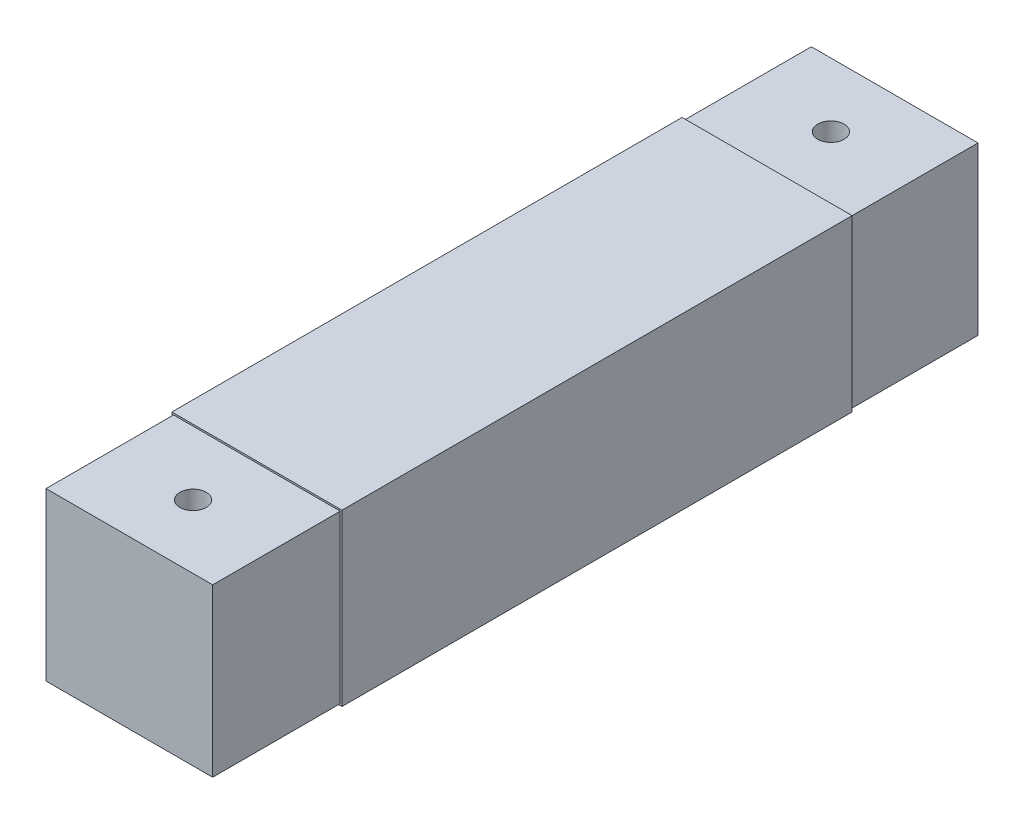
SolidWorks part; units mm, degrees
ref_plane "前视基准面" through (0, 0, 0) normal (0, 0, 1) x (1, 0, 0)
ref_plane "上视基准面" through (0, 0, 0) normal (0, 1, 0) x (1, 0, 0)
ref_plane "右视基准面" through (0, 0, 0) normal (1, 0, 0) x (0, 0, -1)
other "Configuration Table"
sketch "草图1" plane through (0, 0, 0) normal (0, 0, 1) x (1, 0, 0)
  line L1 (0, 0) -> (20, 0)
  line L2 (0, 0) -> (0, 20)
  line L3 (0, 20) -> (20, 20)
  line L4 (20, 0) -> (20, 20)
extrude "凸台-拉伸1" add sketch "草图1" along normal blind 120 contours L2 L1 L4 L3
sketch "草图2" plane through (0, 20, 0) normal (0, 1, 0) x (1, 0, 0)
  line L1 (20, 0) -> (10, 0)
  line L2 (20, 0) -> (20, -20)
  line L3 (20, -20) -> (10, -20)
  line L4 (10, 0) -> (10, -20)
extrude "切除-拉伸1" cut sketch "草图2" against normal blind 120
sketch "草图3" plane through (10, 0, 0) normal (1, 0, 0) x (0, 0, -1)
  line L0 (-20, 20) -> (0, 0)
  circle A0 centre (-10, 10) radius 1.55
extrude "切除-拉伸2" cut sketch "草图3" against normal blind 120 contours L0 A0 | L0 A0
sketch "草图4" plane through (0, 0, 0) normal (-1, 0, 0) x (0, 0, 1)
  circle A0 centre (10, 10) radius 3
extrude "切除-拉伸3" cut sketch "草图4" against normal blind 2
sketch "草图8" plane through (0, 0, 120) normal (0, 0, 1) x (1, 0, 0)
  line L0 (0, 20) -> (0.2, 20)
  line L1 (0, 20) -> (20, 20) construction
  line L2 (0, 20) -> (0, 19.8)
  line L3 (0, 0) -> (0, 20) construction
  line L4 (0, 19.8) -> (20, 19.8)
  line L5 (20, 0) -> (20, 20) construction
  line L6 (0.2, 20) -> (0.2, 19.8)
  line L7 (0.2, 19.8) -> (0.2, 0)
  line L8 (0, 0) -> (20, 0) construction
  line L9 (0.2, 0) -> (0, 0)
  line L10 (0, 0) -> (0, 0.2)
  line L11 (0, 0.2) -> (20, 0.2)
  line L12 (20, 0.2) -> (20, 0)
  line L13 (20, 0) -> (19.8, 0)
  line L14 (19.8, 0) -> (19.8, 20)
  line L15 (19.8, 20) -> (20, 20)
  line L16 (20, 20) -> (20, 0.2)
  line L17 (19.8, 0) -> (0.2, 0)
  line L18 (0.2, 0) -> (19.8, 0)
  line L19 (0, 0.2) -> (0.2, 0.2)
  line L20 (0.2, 0.2) -> (0.2, 0)
  line L21 (0, 0.2) -> (0, 19.8)
  line L22 (0.2, 20) -> (19.8, 20)
  line L23 (19.8, 20) -> (19.8, 19.8)
  line L24 (19.8, 19.8) -> (20, 19.8)
  line M5 (20, 20) -> (0, 20)
  line M6 (0, 20) -> (0, 0)
  line M7 (0, 0) -> (20, 0)
  line M8 (20, 0) -> (20, 20)
extrude "切除-拉伸6" cut sketch "草图8" against normal blind 15 contours L4 L14 L6 M5 | L6 L4 M5 M6 | L11 L7 L4 M6 | L14 L11 L4 M8 | L14 L11 M7 M8 | L14 L11 L7 M7 | L11 L7 M6 M7 | L14 L4 M8 M5
sketch "草图9" plane through (0, 20, 0) normal (0, 1, 0) x (1, 0, 0)
  line L0 (0, -105) -> (0, -45)
  line L1 (0, -105) -> (0, 0) construction
  line L3 (0, -45) -> (20, -45)
  line L4 (0, -45) -> (0, 0)
  line L5 (0, 0) -> (20, 0)
  line L6 (20, -45) -> (20, 0)
  line M6 (0, 0) -> (0, -105)
  line M8 (20, -105) -> (20, -20)
  line M9 (20, -20) -> (10, -20)
  line M10 (10, -20) -> (10, 0)
  line M11 (10, 0) -> (0, 0)
extrude "切除-拉伸7" cut sketch "草图9" against normal blind 20 contours L3 M6 M8 M9 M10 M11 | L6 L5 M9 M10
sketch "草图10" plane through (0, 0, 45) normal (0, 0, -1) x (-1, 0, 0)
  line L0 (-20, 0) -> (-19.8, 0)
  line L1 (0, 0) -> (-20, 0) construction
  line L2 (-19.8, 0) -> (-19.8, 0.2)
  line L6 (0, 20) -> (-0.2, 20)
  line L7 (0, 20) -> (-20, 20) construction
  line L8 (-0.2, 20) -> (-0.2, 19.8)
  line L9 (-19.8, 0.2) -> (-0.2, 0.2)
  line L10 (-19.8, 0.2) -> (-19.8, 19.8)
  line L11 (-19.8, 19.8) -> (-0.2, 19.8)
  line L12 (-0.2, 0.2) -> (-0.2, 19.8)
extrude "凸台-拉伸2" add sketch "草图10" along normal blind 15 contours L10 L9 L12 L11
sketch "草图11" plane through (0, 19.8, 0) normal (0, 1, 0) x (1, 0, 0)
  line L0 (0, -105) -> (0, -120)
  line L1 (0, -120) -> (19.9951, -120)
  line L2 (19.9951, -120) -> (20, -105)
  line L3 (20, -105) -> (0, -105)
  line L4 (0, -105) -> (19.9951, -120)
  circle A0 centre (9.9976, -112.5) radius 1.55
extrude "切除-拉伸8" cut sketch "草图11" against normal blind 20 contours L4 A0 | L4 A0
sketch "草图12" plane through (0, 19.8, 0) normal (0, 1, 0) x (1, 0, 0)
  line L0 (0, -45) -> (0, -30)
  line L1 (0, -30) -> (20, -30)
  line L2 (20, -30) -> (20, -45)
  line L3 (20, -45) -> (0, -30)
  circle A0 centre (10, -37.5) radius 1.55
extrude "切除-拉伸9" cut sketch "草图12" against normal blind 20 contours L3 A0 | L3 A0
